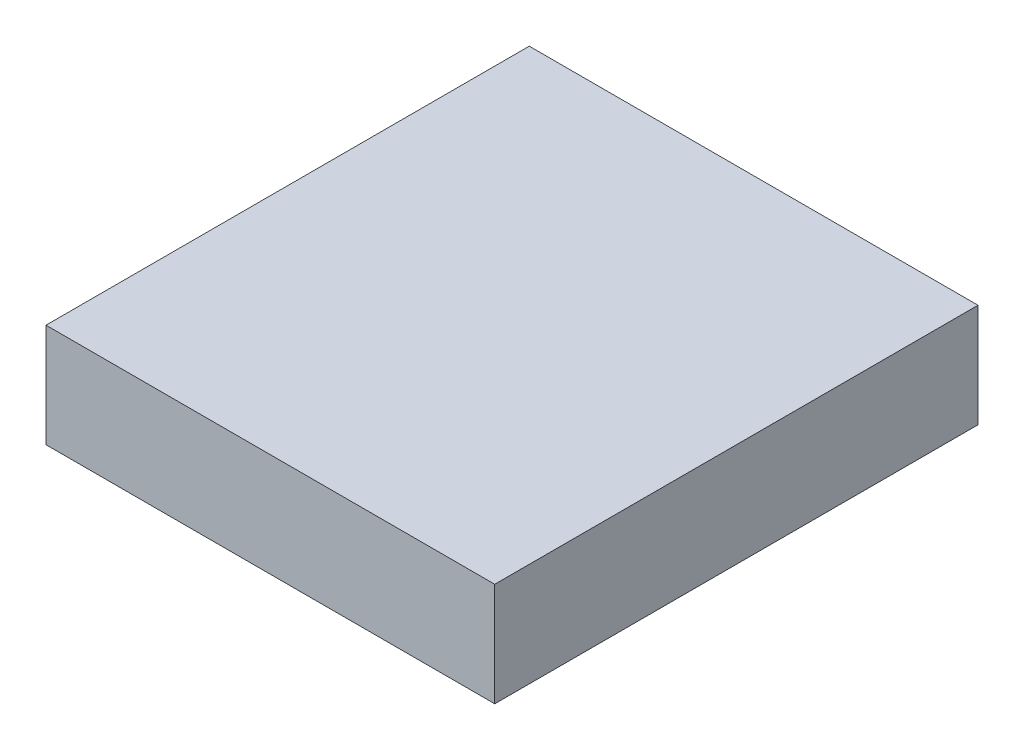
SolidWorks part; units mm, degrees
ref_plane "Front Plane" through (0, 0, 0) normal (0, 0, 1) x (1, 0, 0)
ref_plane "Top Plane" through (0, 0, 0) normal (0, 1, 0) x (1, 0, 0)
ref_plane "Right Plane" through (0, 0, 0) normal (1, 0, 0) x (0, 0, -1)
sketch "Sketch1" plane through (0, 0, 0) normal (0, 1, 0) x (1, 0, 0)
  line L1 (-41.275, 44.45) -> (41.275, 44.45)
  line L2 (-41.275, 44.45) -> (-41.275, -44.45)
  line L3 (-41.275, -44.45) -> (41.275, -44.45)
  line L4 (41.275, 44.45) -> (41.275, -44.45)
  line L5 (-41.275, 44.45) -> (41.275, -44.45) construction
  line L6 (-41.275, -44.45) -> (41.275, 44.45) construction
  point P0 (0, 0)
extrude "Boss-Extrude1" add sketch "Sketch1" along normal blind 19.05
